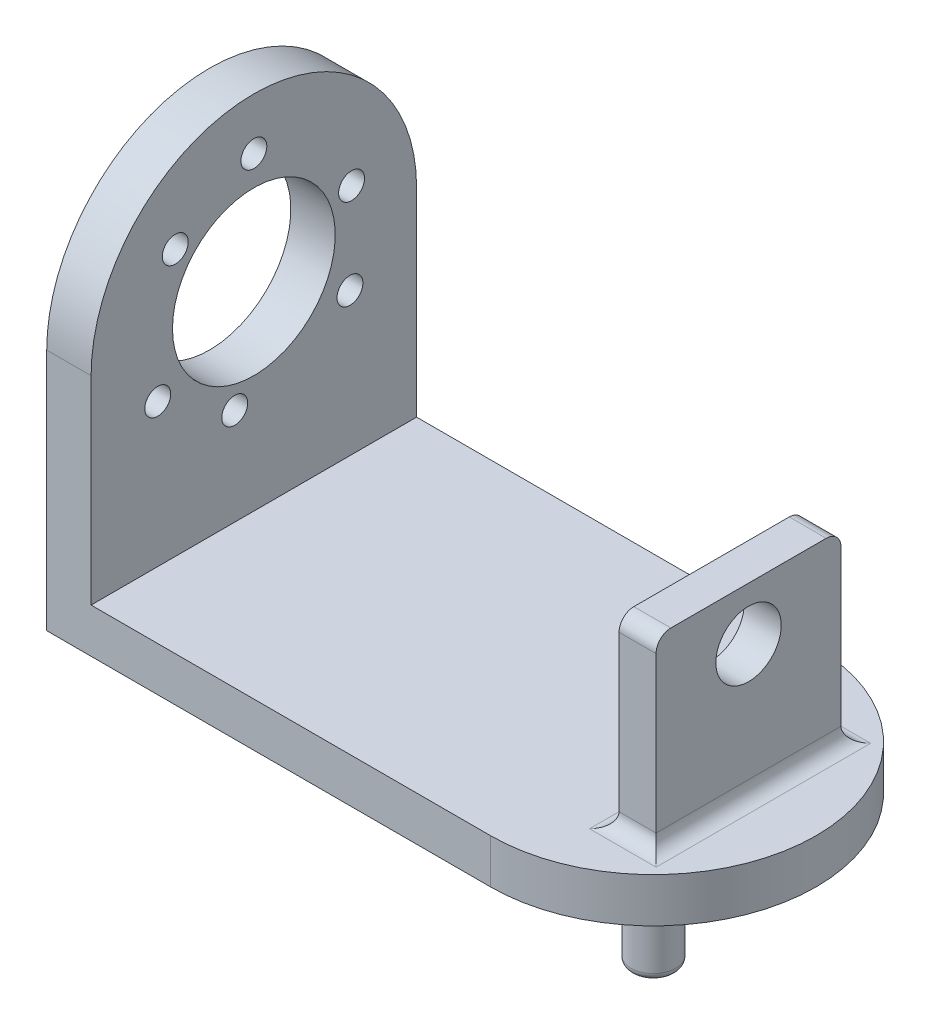
SolidWorks part; units mm, degrees
material "PLA-custom"
ref_plane "Front Plane" through (0, 0, 0) normal (0, 0, 1) x (1, 0, 0)
ref_plane "Top Plane" through (0, 0, 0) normal (0, 1, 0) x (1, 0, 0)
ref_plane "Right Plane" through (0, 0, 0) normal (1, 0, 0) x (0, 0, -1)
sketch "Sketch1" plane through (0, 0, 0) normal (0, 1, 0) x (1, 0, 0)
  line L0 (0, 0) -> (-60, 0) construction
  line L1 (0, -22) -> (-60, -22)
  line L2 (0, 22) -> (-60, 22)
  line L3 (-60, 22) -> (-60, -22)
  arc A0 (0, -22) -> (0, 22) centre (0, 0) ccw
  point P3 (-30, 0)
  dimension "D2" = 22
  dimension "D1" = 60
extrude "Boss-Extrude1" add sketch "Sketch1" along normal blind 6
sketch "Sketch2" plane through (-60, 0, 0) normal (-1, 0, 0) x (0, 0, 1)
  line L0 (0, 6) -> (0, 32.8484) construction
  line L1 (-22, 6) -> (22, 6) construction
  line L2 (-22, 6) -> (-22, 32.8473)
  line L3 (22, 6) -> (22, 32.8484)
  line L4 (-22, 6) -> (22, 6)
  arc A1 (22, 32.8484) -> (-22, 32.8473) centre (0, 32.8484) ccw
  point P5 (0, 19.4242)
  dimension "D1" = 22
extrude "Boss-Extrude2" add sketch "Sketch2" against normal blind 6
sketch "Sketch3" plane through (-60, 0, 0) normal (-1, 0, 0) x (0, 0, 1)
  circle A0 centre (0, 32.8484) radius 11
  circle A1 centre (0, 32.8484) radius 15 construction
  circle A2 centre (0, 47.8484) radius 1.75
  circle A3 centre (12.9904, 25.3484) radius 1.75
  circle A4 centre (-12.9904, 25.3484) radius 1.75
  circle A5 centre (0, 32.8484) radius 14 construction
  circle A6 centre (10.6237, 41.9663) radius 1.75
  circle A7 centre (2.5845, 19.089) radius 1.75
  circle A8 centre (-13.2082, 37.4899) radius 1.75
  point P13 (0, 32.8484)
  point P21 (0, 32.8484)
  dimension "D1" = 22
  dimension "D2" = 30
  dimension "D3" = 3.5
  dimension "D5" = 28
  dimension "D6" = 3.5
  dimension "D4" = 3
  dimension "D7" = 3
extrude "Cut-Extrude1" cut sketch "Sketch3" against normal blind 6
sketch "Sketch4" plane through (0, 0, 0) normal (0, -1, 0) x (1, 0, 0)
  circle A0 centre (0, 0) radius 3.025
  dimension "D1" = 6.05
extrude "Boss-Extrude3" add sketch "Sketch4" along normal blind 20
fillet "Fillet1" radius 10 1 edges at (0, 0, 3.025)
fillet "Fillet2" radius 1 1 edges at (0, -20, -3.025)
sketch "Sketch5" plane through (0, 6, 0) normal (0, 1, 0) x (1, 0, 0)
  line L1 (7.8646, -12.5) -> (12.8646, -12.5)
  line L2 (7.8646, -12.5) -> (7.8646, 12.5)
  line L3 (7.8646, 12.5) -> (12.8646, 12.5)
  line L4 (12.8646, -12.5) -> (12.8646, 12.5)
  point P0 (10.3646, 0)
  dimension "D1" = 5
  dimension "D2" = 25
extrude "Boss-Extrude4" add sketch "Sketch5" along normal blind 25
sketch "Sketch6" plane through (12.8646, 0, 0) normal (1, 0, 0) x (0, 0, -1)
  circle A0 centre (0, 23.8788) radius 4.4196
extrude "Cut-Extrude2" cut sketch "Sketch6" against normal up to next
fillet "Fillet3" radius 2 6 edges at (10.3646, 31, 12.5) (10.3646, 31, -12.5) (10.3646, 6, 12.5) (7.8646, 6, 0) (10.3646, 6, -12.5) (12.8646, 6, 0)
